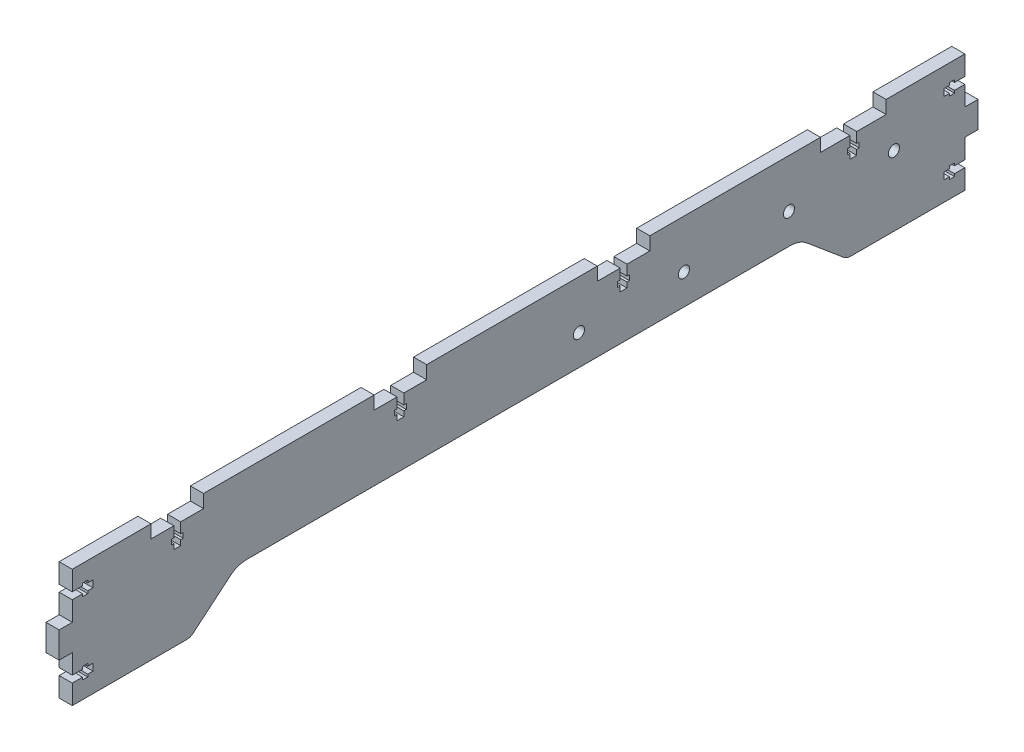
SolidWorks part; units mm, degrees
material "Pine"
ref_plane "Front Plane" through (0, 0, 0) normal (0, 0, 1) x (1, 0, 0)
ref_plane "Top Plane" through (0, 0, 0) normal (0, 1, 0) x (1, 0, 0)
ref_plane "Right Plane" through (0, 0, 0) normal (1, 0, 0) x (0, 0, -1)
ref_plane "Plane1" through (6.35, 0, 0) normal (1, 0, 0) x (0, 0, -1)
sketch "Sketch1" plane through (6.35, 0, 0) normal (1, 0, 0) x (0, 0, -1)
  line L0 (-44.45, 57.15) -> (-44.45, 50.8)
  line L1 (-44.45, 50.8) -> (-55.5, 50.8)
  line L2 (-55.5, 50.8) -> (-55.5, 45.8)
  line L3 (-55.5, 45.8) -> (-54.3, 45.8)
  line L4 (-54.3, 45.8) -> (-54.3, 43.3)
  line L5 (-54.3, 43.3) -> (-55.5, 43.3)
  line L6 (-55.5, 43.3) -> (-55.5, 40.8)
  line L7 (-55.5, 40.8) -> (-58.8, 40.8)
  line L8 (-58.8, 40.8) -> (-58.8, 43.3)
  line L9 (-58.8, 43.3) -> (-60, 43.3)
  line L10 (-60, 43.3) -> (-60, 45.8)
  line L11 (-60, 45.8) -> (-58.8, 45.8)
  line L12 (-58.8, 45.8) -> (-58.8, 50.8)
  line L13 (-58.8, 50.8) -> (-69.85, 50.8)
  line L14 (-69.85, 50.8) -> (-69.85, 57.15)
  line L15 (-69.85, 57.15) -> (-152.4, 57.15)
  line L16 (-152.4, 57.15) -> (-152.4, 50.8)
  line L17 (-152.4, 50.8) -> (-163.45, 50.8)
  line L18 (-163.45, 50.8) -> (-163.45, 45.8)
  line L19 (-163.45, 45.8) -> (-162.25, 45.8)
  line L20 (-162.25, 45.8) -> (-162.25, 43.3)
  line L21 (-162.25, 43.3) -> (-163.45, 43.3)
  line L22 (-163.45, 43.3) -> (-163.45, 40.8)
  line L23 (-163.45, 40.8) -> (-166.75, 40.8)
  line L24 (-166.75, 40.8) -> (-166.75, 43.3)
  line L25 (-166.75, 43.3) -> (-167.95, 43.3)
  line L26 (-167.95, 43.3) -> (-167.95, 45.8)
  line L27 (-167.95, 45.8) -> (-166.75, 45.8)
  line L28 (-166.75, 45.8) -> (-166.75, 50.8)
  line L29 (-166.75, 50.8) -> (-177.8, 50.8)
  line L30 (-177.8, 50.8) -> (-177.8, 57.15)
  line L31 (-177.8, 57.15) -> (-215.9, 57.15)
  line L32 (-215.9, 57.15) -> (-215.9, 47.6875)
  line L33 (-215.9, 47.6875) -> (-210.9, 47.6875)
  line L34 (-210.9, 47.6875) -> (-210.9, 48.8875)
  line L35 (-210.9, 48.8875) -> (-208.4, 48.8875)
  line L36 (-208.4, 48.8875) -> (-208.4, 47.6875)
  line L37 (-208.4, 47.6875) -> (-205.9, 47.6875)
  line L38 (-205.9, 47.6875) -> (-205.9, 44.3875)
  line L39 (-205.9, 44.3875) -> (-208.4, 44.3875)
  line L40 (-208.4, 44.3875) -> (-208.4, 43.1875)
  line L41 (-208.4, 43.1875) -> (-210.9, 43.1875)
  line L42 (-210.9, 43.1875) -> (-210.9, 44.3875)
  line L43 (-210.9, 44.3875) -> (-215.9, 44.3875)
  line L44 (-215.9, 44.3875) -> (-215.9, 34.925)
  line L45 (-215.9, 34.925) -> (-222.25, 34.925)
  line L46 (-222.25, 34.925) -> (-222.25, 22.225)
  line L47 (-222.25, 22.225) -> (-215.9, 22.225)
  line L48 (-215.9, 22.225) -> (-215.9, 12.7625)
  line L49 (-215.9, 12.7625) -> (-210.9, 12.7625)
  line L50 (-210.9, 12.7625) -> (-210.9, 13.9625)
  line L51 (-210.9, 13.9625) -> (-208.4, 13.9625)
  line L52 (-208.4, 13.9625) -> (-208.4, 12.7625)
  line L53 (-208.4, 12.7625) -> (-205.9, 12.7625)
  line L54 (-205.9, 12.7625) -> (-205.9, 9.4625)
  line L55 (-205.9, 9.4625) -> (-208.4, 9.4625)
  line L56 (-208.4, 9.4625) -> (-208.4, 8.2625)
  line L57 (-208.4, 8.2625) -> (-210.9, 8.2625)
  line L58 (-210.9, 8.2625) -> (-210.9, 9.4625)
  line L59 (-210.9, 9.4625) -> (-215.9, 9.4625)
  line L60 (-215.9, 9.4625) -> (-215.9, 0)
  line L61 (-215.9, 0) -> (-160.599, 0)
  line L62 (-157.3336, 1.1885) -> (-139.5881, 16.0788)
  line L63 (-131.4247, 19.05) -> (131.4247, 19.05)
  line L64 (139.5881, 16.0788) -> (157.3336, 1.1885)
  line L65 (160.599, 0) -> (215.9, 0)
  line L66 (215.9, 0) -> (215.9, 9.4625)
  line L67 (215.9, 9.4625) -> (210.9, 9.4625)
  line L68 (210.9, 9.4625) -> (210.9, 8.2625)
  line L69 (210.9, 8.2625) -> (208.4, 8.2625)
  line L70 (208.4, 8.2625) -> (208.4, 9.4625)
  line L71 (208.4, 9.4625) -> (205.9, 9.4625)
  line L72 (205.9, 9.4625) -> (205.9, 12.7625)
  line L73 (205.9, 12.7625) -> (208.4, 12.7625)
  line L74 (208.4, 12.7625) -> (208.4, 13.9625)
  line L75 (208.4, 13.9625) -> (210.9, 13.9625)
  line L76 (210.9, 13.9625) -> (210.9, 12.7625)
  line L77 (210.9, 12.7625) -> (215.9, 12.7625)
  line L78 (215.9, 12.7625) -> (215.9, 22.225)
  line L79 (215.9, 22.225) -> (222.25, 22.225)
  line L80 (222.25, 22.225) -> (222.25, 34.925)
  line L81 (222.25, 34.925) -> (215.9, 34.925)
  line L82 (215.9, 34.925) -> (215.9, 44.3875)
  line L83 (215.9, 44.3875) -> (210.9, 44.3875)
  line L84 (210.9, 44.3875) -> (210.9, 43.1875)
  line L85 (210.9, 43.1875) -> (208.4, 43.1875)
  line L86 (208.4, 43.1875) -> (208.4, 44.3875)
  line L87 (208.4, 44.3875) -> (205.9, 44.3875)
  line L88 (205.9, 44.3875) -> (205.9, 47.6875)
  line L89 (205.9, 47.6875) -> (208.4, 47.6875)
  line L90 (208.4, 47.6875) -> (208.4, 48.8875)
  line L91 (208.4, 48.8875) -> (210.9, 48.8875)
  line L92 (210.9, 48.8875) -> (210.9, 47.6875)
  line L93 (210.9, 47.6875) -> (215.9, 47.6875)
  line L94 (215.9, 47.6875) -> (215.9, 57.15)
  line L95 (215.9, 57.15) -> (177.8, 57.15)
  line L96 (177.8, 57.15) -> (177.8, 50.8)
  line L97 (177.8, 50.8) -> (163.575, 50.8)
  line L98 (163.575, 50.8) -> (163.575, 45.8)
  line L99 (163.575, 45.8) -> (164.775, 45.8)
  line L100 (164.775, 45.8) -> (164.775, 43.3)
  line L101 (164.775, 43.3) -> (163.575, 43.3)
  line L102 (163.575, 43.3) -> (163.575, 40.8)
  line L103 (163.575, 40.8) -> (160.275, 40.8)
  line L104 (160.275, 40.8) -> (160.275, 43.3)
  line L105 (160.275, 43.3) -> (159.075, 43.3)
  line L106 (159.075, 43.3) -> (159.075, 45.8)
  line L107 (159.075, 45.8) -> (160.275, 45.8)
  line L108 (160.275, 45.8) -> (160.275, 50.8)
  line L109 (160.275, 50.8) -> (146.05, 50.8)
  line L110 (146.05, 50.8) -> (146.05, 57.15)
  line L111 (146.05, 57.15) -> (63.5, 57.15)
  line L112 (63.5, 57.15) -> (63.5, 50.8)
  line L113 (63.5, 50.8) -> (52.45, 50.8)
  line L114 (52.45, 50.8) -> (52.45, 45.8)
  line L115 (52.45, 45.8) -> (53.65, 45.8)
  line L116 (53.65, 45.8) -> (53.65, 43.3)
  line L117 (53.65, 43.3) -> (52.45, 43.3)
  line L118 (52.45, 43.3) -> (52.45, 40.8)
  line L119 (52.45, 40.8) -> (49.15, 40.8)
  line L120 (49.15, 40.8) -> (49.15, 43.3)
  line L121 (49.15, 43.3) -> (47.95, 43.3)
  line L122 (47.95, 43.3) -> (47.95, 45.8)
  line L123 (47.95, 45.8) -> (49.15, 45.8)
  line L124 (49.15, 45.8) -> (49.15, 50.8)
  line L125 (49.15, 50.8) -> (38.1, 50.8)
  line L126 (38.1, 50.8) -> (38.1, 57.15)
  line L127 (38.1, 57.15) -> (-44.45, 57.15)
  circle A0 centre (79.9883, 33.749) radius 2.7
  circle A1 centre (130.7883, 33.749) radius 2.7
  circle A2 centre (29.1883, 33.749) radius 2.7
  circle A3 centre (181.5883, 33.749) radius 2.7
  arc A4 (-160.599, 0) -> (-157.3336, 1.1885) centre (-160.599, 5.08) ccw
  arc A5 (-139.5881, 16.0788) -> (-131.4247, 19.05) centre (-131.4247, 6.35) cw
  arc A6 (131.4247, 19.05) -> (139.5881, 16.0788) centre (131.4247, 6.35) cw
  arc A7 (157.3336, 1.1885) -> (160.599, 0) centre (160.599, 5.08) ccw
extrude "Boss-Extrude1" add sketch "Sketch1" against normal blind 6.35
